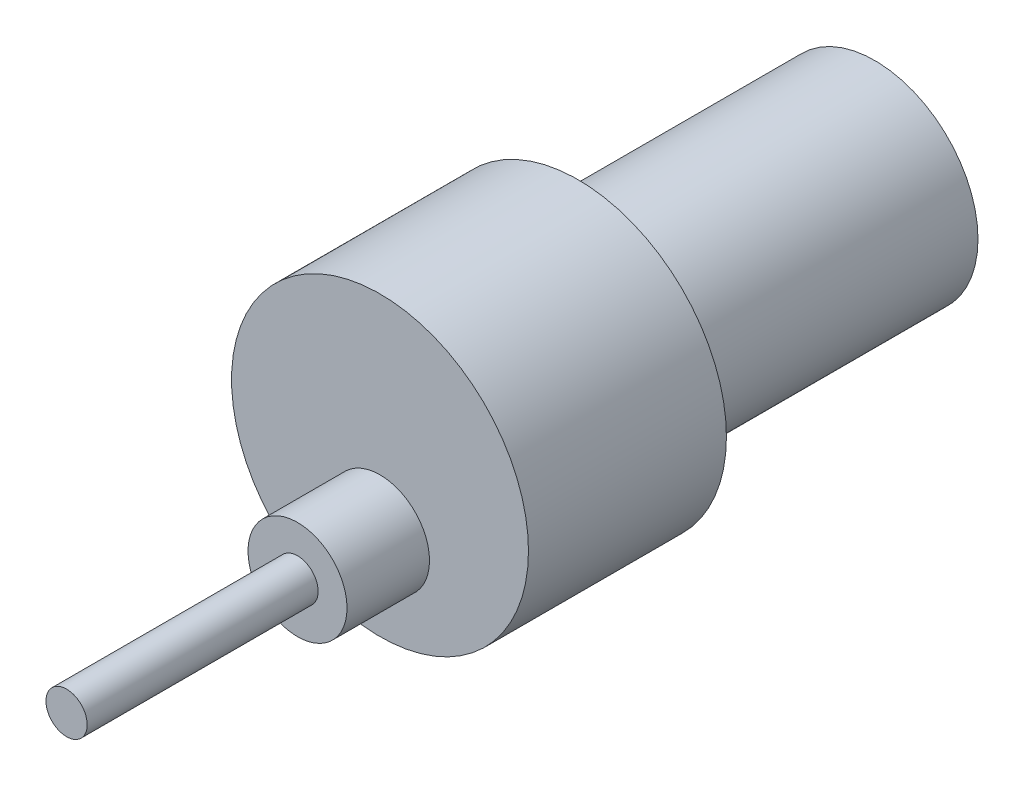
SolidWorks part; units mm, degrees
ref_plane "Front Plane" through (0, 0, 0) normal (0, 0, 1) x (1, 0, 0)
ref_plane "Top Plane" through (0, 0, 0) normal (0, 1, 0) x (1, 0, 0)
ref_plane "Right Plane" through (0, 0, 0) normal (1, 0, 0) x (0, 0, -1)
sketch "Sketch1" plane through (0, 0, 0) normal (0, 0, 1) x (1, 0, 0)
  circle A0 centre (0, 0) radius 12.5
  dimension "D1" = 25
extrude "Boss-Extrude1" add sketch "Sketch1" along normal blind 36
sketch "Sketch2" plane through (0, 0, 0) normal (0, 0, -1) x (-1, 0, 0)
  circle A0 centre (0, 0) radius 5
extrude "Boss-Extrude2" add sketch "Sketch2" along normal blind 4
sketch "Sketch3" plane through (0, 0, 36) normal (0, 0, 1) x (1, 0, 0)
  circle A0 centre (0, 0) radius 18
extrude "Boss-Extrude3" add sketch "Sketch3" along normal blind 24
sketch "Sketch4" plane through (0, 0, 60) normal (0, 0, 1) x (1, 0, 0)
  line L0 (0, 21.4029) -> (0, -23.2136) construction
sketch "Sketch5" plane through (0, 0, 60) normal (0, 0, 1) x (1, 0, 0)
  line L0 (0, 21.4029) -> (0, -23.2136) construction
  circle A0 centre (0, -7) radius 6
  point P5 (0, 0)
  point P8 (0, 0)
extrude "Boss-Extrude4" add sketch "Sketch5" along normal blind 10
sketch "Sketch7" plane through (0, 0, 70) normal (0, 0, 1) x (1, 0, 0)
  line L0 (0, 21.4029) -> (0, -23.2136) construction
  circle A0 centre (0, -7) radius 2.5
  circle A1 centre (0, -7) radius 6 construction
  dimension "D1" = 0
extrude "Boss-Extrude5" add sketch "Sketch7" along normal blind 28
